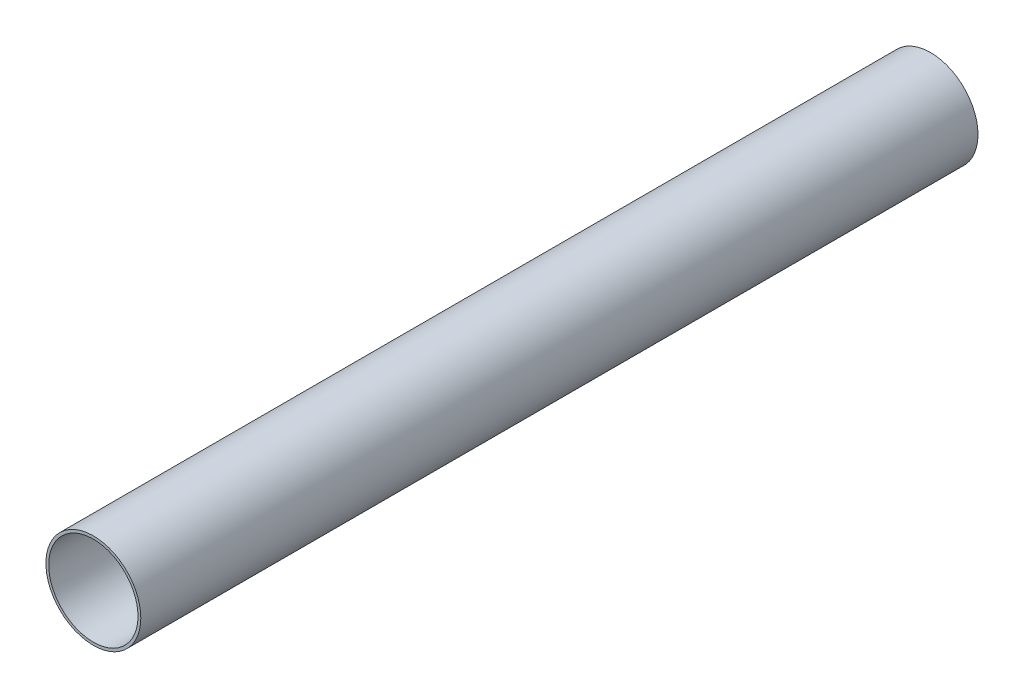
SolidWorks part; units mm, degrees
ref_plane "Front Plane" through (0, 0, 0) normal (0, 0, 1) x (1, 0, 0)
ref_plane "Top Plane" through (0, 0, 0) normal (0, 1, 0) x (1, 0, 0)
ref_plane "Right Plane" through (0, 0, 0) normal (1, 0, 0) x (0, 0, -1)
sketch "Sketch1" plane through (0, 0, 0) normal (0, 0, 1) x (1, 0, 0)
  circle A0 centre (0, 0) radius 16
  circle A1 centre (0, 0) radius 17
  dimension "D1" = 32
  dimension "D2" = 34
extrude "Boss-Extrude1" add sketch "Sketch1" along normal blind 300
